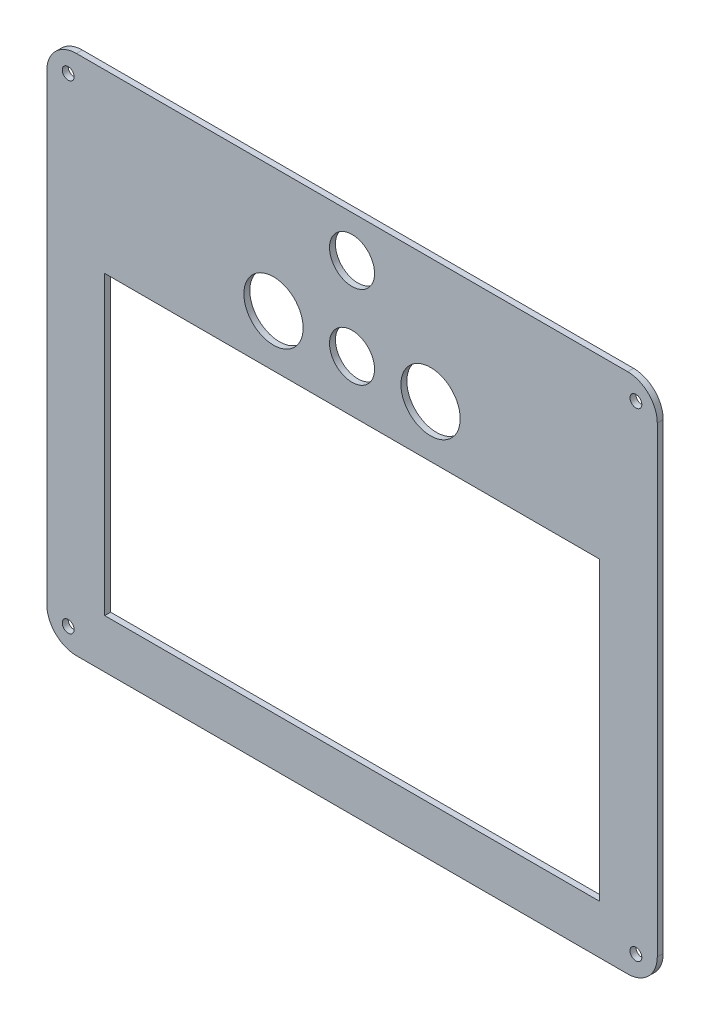
SolidWorks part; units mm, degrees
ref_plane "Front Plane" through (0, 0, 0) normal (0, 0, 1) x (1, 0, 0)
ref_plane "Top Plane" through (0, 0, 0) normal (0, 1, 0) x (1, 0, 0)
ref_plane "Right Plane" through (0, 0, 0) normal (1, 0, 0) x (0, 0, -1)
sketch "Sketch1" plane through (0, 0, 0) normal (0, 0, 1) x (1, 0, 0)
  line L1 (0, 0) -> (206, 0)
  line L2 (0, 0) -> (0, -176)
  line L3 (0, -176) -> (206, -176)
  line L4 (206, 0) -> (206, -176)
  dimension "D1" = 206
  dimension "D2" = 176
extrude "Boss-Extrude1" add sketch "Sketch1" along normal blind 2
fillet "Fillet1" radius 10 4 edges at (206, -176, 1) (0, -176, 1) (0, 0, 1) (206, 0, 1)
sketch "Sketch2" plane through (0, 0, 0) normal (0, 0, -1) x (-1, 0, 0)
  line L0 (-196, 0) -> (-10, 0) construction
  line L1 (-206, -166) -> (-206, -10) construction
  line L2 (0, -10) -> (0, -166) construction
  line L3 (-10, -176) -> (-196, -176) construction
  circle A0 centre (-198.7855, -7.2145) radius 2
  circle A4 centre (-7.2145, -7.2145) radius 2
  circle A5 centre (-7.2145, -168.7855) radius 2
  circle A6 centre (-198.7855, -168.7855) radius 2
  dimension "D1" = 7.2145
  dimension "D2" = 7.2145
  dimension "D3" = 4
  dimension "D4" = 4
  dimension "D5" = 7.2145
  dimension "D6" = 4
  dimension "D7" = 7.2145
  dimension "D8" = 4
  dimension "D9" = 7.2145
  dimension "D10" = 7.2145
  dimension "D11" = 4
  dimension "D12" = 7.2145
  dimension "D13" = 7.2145
extrude "Cut-Extrude1" cut sketch "Sketch2" against normal blind 5
sketch "Sketch3" plane through (0, 0, 0) normal (0, 0, -1) x (-1, 0, 0)
  line L0 (0, -10) -> (0, -166) construction
  line L1 (-196, 0) -> (-10, 0) construction
  line L2 (-206, -166) -> (-206, -10) construction
  circle A0 centre (-103, -14) radius 7.6
  circle A1 centre (-129.5, -42) radius 10
  circle A2 centre (-103, -42) radius 7.6
  circle A3 centre (-76.5, -42) radius 10
  dimension "D1" = 103
  dimension "D2" = 14
  dimension "D3" = 76.5
  dimension "D4" = 76.5
  dimension "D5" = 42
  dimension "D6" = 42
  dimension "D7" = 42
  dimension "D8" = 103
  dimension "D9" = 15.2
  dimension "D10" = 15.2
  dimension "D11" = 20
  dimension "D12" = 20
extrude "Cut-Extrude2" cut sketch "Sketch3" against normal blind 5
sketch "Sketch4" plane through (0, 0, 2) normal (0, 0, 1) x (1, 0, 0)
  line L0 (103, 0) -> (103, -176)
  line L1 (196, 0) -> (10, 0) construction
  line L2 (10, -176) -> (196, -176) construction
  line L4 (19.55, -59.5) -> (186.45, -59.5)
  line L5 (19.55, -59.5) -> (19.55, -159.5)
  line L6 (19.55, -159.5) -> (186.45, -159.5)
  line L7 (186.45, -59.5) -> (186.45, -159.5)
  line L8 (19.55, -59.5) -> (186.45, -159.5) construction
  line L9 (19.55, -159.5) -> (186.45, -59.5) construction
  point P6 (103, -109.5)
  dimension "D1" = 100
  dimension "D2" = 166.9
  dimension "D3" = 109.5
extrude "Cut-Extrude3" cut sketch "Sketch4" against normal blind 10 contours L5 L6 L0 L4 | L7 L4 L0 L6
